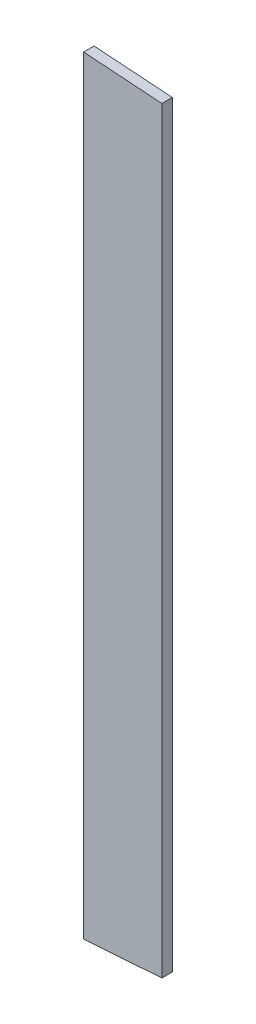
SolidWorks part; units mm, degrees
ref_plane "Front Plane" through (0, 0, 0) normal (0, 0, 1) x (1, 0, 0)
ref_plane "Top Plane" through (0, 0, 0) normal (0, 1, 0) x (1, 0, 0)
ref_plane "Right Plane" through (0, 0, 0) normal (1, 0, 0) x (0, 0, -1)
sketch "Sketch1" plane through (0, 0, 3895.25) normal (0, 0, 1) x (1, 0, 0)
  line L0 (-49.7697, 346.1083) -> (-64.7697, 345.0594)
  line L1 (-140.9262, 339.734) -> (58.5866, 353.6853) construction
  line L2 (-64.7697, 345.0594) -> (-64.7697, 492.4158)
  line L3 (58.5866, 483.7899) -> (-140.9262, 497.7412) construction
  line L4 (-64.7697, 492.4158) -> (-49.7697, 491.3669)
  line L5 (-49.7697, 491.3669) -> (-49.7697, 346.1083)
  dimension "D1" = 15
extrude "Boss-Extrude1" add sketch "Sketch1" along normal blind 2
ref_plane "Plane1" through (-57.2697, 0, 0) normal (1, 0, 0) x (0, 0, -1)
ref_plane "Plane2" through (0, 418.7376, 0) normal (0, 1, 0) x (1, 0, 0)
